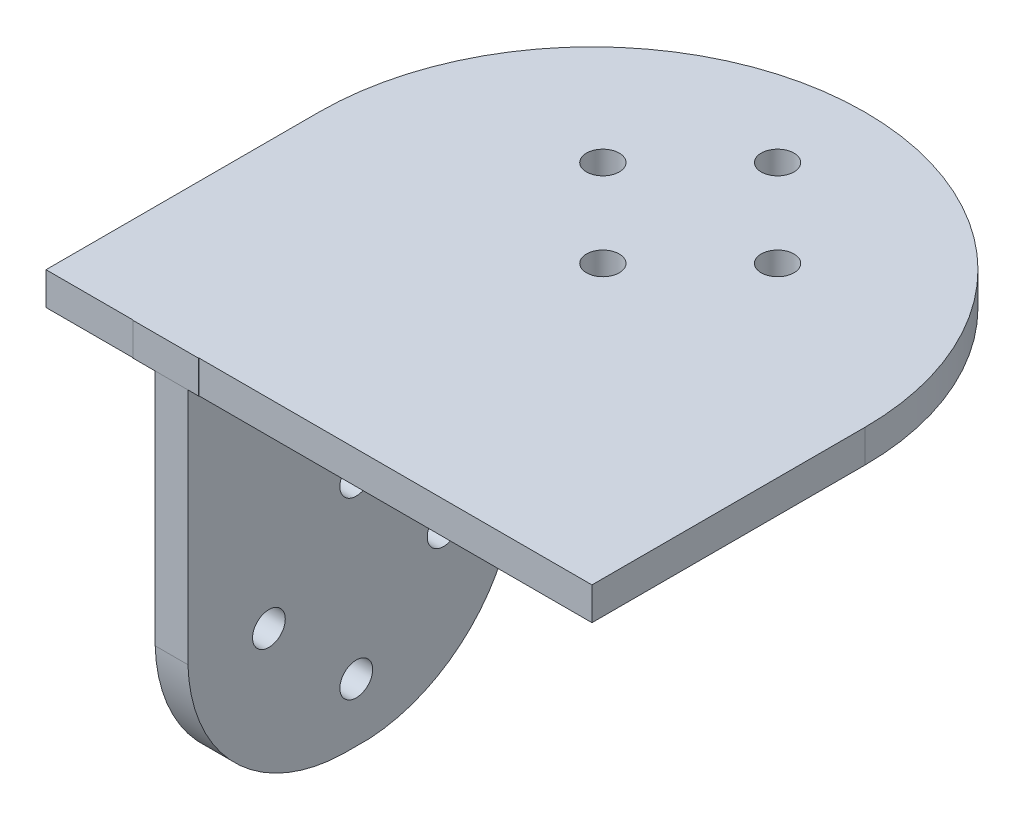
SolidWorks part; units mm, degrees
ref_plane "Plan de face" through (0, 0, 0) normal (0, 0, 1) x (1, 0, 0)
ref_plane "Plan de dessus" through (0, 0, 0) normal (0, 1, 0) x (1, 0, 0)
ref_plane "Plan de droite" through (0, 0, 0) normal (1, 0, 0) x (0, 0, -1)
sketch "Esquisse2" plane through (0, 0, 0) normal (0, 1, 0) x (1, 0, 0)
  line L0 (-25, 0) -> (25, 0) construction
  line L1 (-25, 0) -> (-25, -25)
  line L2 (25, 0) -> (25, -25)
  line L3 (25, -25) -> (-25, -25)
  arc A0 (25, 0) -> (-25, 0) centre (0, 0) ccw
  dimension "D1" = 50
  dimension "D2" = 25
  dimension "D3" = 25
extrude "Boss.-Extru.1" add sketch "Esquisse2" along normal blind 3
sketch "Esquisse4" plane through (0, 0, 0) normal (0, -1, 0) x (1, 0, 0)
  line L0 (-25, 25) -> (-15, 25) construction
  line L1 (-25, 25) -> (25, 25) construction
  line L2 (-15, 25) -> (-11, 25)
  line L7 (-15, 25) -> (-15, 0)
  line L8 (-15, 0) -> (-11, 0)
  line L9 (-11, 0) -> (-11, 25)
  dimension "D1" = 10
  dimension "D2" = 4
extrude "Enlèv. mat.-Extru.1" cut sketch "Esquisse4" against normal blind 3
sketch "Esquisse5" plane through (0, 0, 0) normal (0, -1, 0) x (1, 0, 0)
  line L0 (0, -25) -> (0, -23) construction
  line L1 (0, -23) -> (0, -20) construction
  line L2 (0, -20) -> (0, 2) construction
  line L3 (0, 2) -> (0, 5) construction
  line L4 (0, -9) -> (-30.2244, -9) construction
  line L5 (-30.2244, -9) -> (30.2203, -9) construction
  line L6 (30.2203, -9) -> (0, -9) construction
  line L7 (0, -9) -> (-12.5953, -21.5953) construction
  line L8 (0, -9) -> (12.5953, -21.5953) construction
  line L9 (0, -9) -> (-6.5, -9)
  line L10 (0, -9) -> (6.5, -9)
  line L11 (0, -9) -> (0, -2.5)
  line L12 (0, -9) -> (0, -15.5)
  line L13 (6.5, -9) -> (8, -9)
  line L14 (0, -15.5) -> (0, -17)
  line L15 (-6.5, -9) -> (-8, -9)
  line L16 (0, -2.5) -> (0, -1)
  arc A0 (-25, 0) -> (25, 0) centre (0, 0) ccw construction
  circle A5 centre (8, -9) radius 1.5
  circle A6 centre (-8, -9) radius 1.5
  circle A7 centre (0, -17) radius 1.5
  circle A8 centre (0, -1) radius 1.5
  dimension "D1" = 2
  dimension "D2" = 3
  dimension "D3" = 22
  dimension "D4" = 3
  dimension "D5" = 6.5
  dimension "D6" = 6.5
  dimension "D7" = 6.5
  dimension "D8" = 6.5
extrude "Enlèv. mat.-Extru.2" cut sketch "Esquisse5" against normal blind 3
sketch "Esquisse9" plane through (-15, 0, 0) normal (1, 0, 0) x (0, 0, -1)
  line L0 (-25, 3) -> (-25, 0)
  line L1 (-25, 3) -> (0.089, 3)
  line L2 (-25, 0) -> (0.089, 0)
  line L3 (0.089, 3) -> (0.089, 0)
extrude "Boss.-Extru.5" add sketch "Esquisse9" along normal blind 6
sketch "Esquisse10" plane through (0, 0, 0) normal (0, -1, 0) x (1, 0, 0)
  line L0 (-25, 25) -> (-15, 25)
  line L1 (-25, 25) -> (25, 25) construction
  line L2 (-15, 25) -> (-15, -5)
  line L3 (-15, -5) -> (-12, -5)
  line L4 (-12, -5) -> (-12, 25)
  line L5 (-12, 25) -> (-15, 25)
  line M2 (25, 25) -> (-25, 25)
extrude "Boss.-Extru.6" add sketch "Esquisse10" along normal blind 36 contours L3 L4 L2 M2
sketch "Esquisse12" plane through (-12, 0, 0) normal (1, 0, 0) x (0, 0, 1)
  line L0 (-5, 36) -> (-5, 0) construction
  line L1 (-5, 36) -> (25, 36) construction
  line L2 (25, 36) -> (25, 0) construction
  line L3 (-5, 22.6624) -> (-5, 36)
  line L4 (-5, 36) -> (25, 36)
  line L5 (25, 36) -> (25, 21.8312)
  arc A0 (-5, 22.6624) -> (10, 36) centre (9.1688, 21.8312) cw
  circle A5 centre (17.5856, 22.6624) radius 1.5
  circle A6 centre (1.5856, 22.6624) radius 1.5
  circle A7 centre (9.5856, 14.6624) radius 1.5
  circle A8 centre (9.5856, 30.6624) radius 1.5
  arc A9 (10, 36) -> (25, 21.8312) centre (10.4156, 21.4156) cw
  line M39 (25, 0) -> (25, 36)
  line M40 (25, 36) -> (-5, 36)
  line M41 (-5, 36) -> (-5, 0)
extrude "Enlèv. mat.-Extru.3" cut sketch "Esquisse12" against normal blind 36 contours A0 M41 M40 | A9 M40 M39 | A8 | A6 | A7 | A5
sketch "Esquisse6" plane through (-11, 0, 0) normal (-1, 0, 0) x (0, 0, 1)
  line L0 (25, 3) -> (25, -32)
  line L1 (25, 3) -> (0, 3) construction
  line L2 (0, 3) -> (25, 3) construction
  line L3 (25, 3) -> (25, -14.5) construction
  line L4 (25, 3) -> (12.5, 3) construction
  line L5 (12.5, 3) -> (12.5, -14.5) construction
  line L6 (12.5, -14.5) -> (25, -14.5) construction
  line L7 (25, -14.5) -> (0, -14.5) construction
  line L8 (0, -14.5) -> (0, 3)
  line L9 (0, 3) -> (25, 3)
  arc A0 (0, -14.5) -> (25, -14.5) centre (12.5, -14.5) ccw
  dimension "D1" = 35
  dimension "D2" = 25
  dimension "D3" = 17.5
sketch "Esquisse8" plane through (-11, 0, 0) normal (-1, 0, 0) x (0, 0, 1)
  line L0 (0, 0) -> (0, 3)
  line L1 (0, 0) -> (25.0333, 0)
  line L2 (0, 3) -> (25.0333, 3)
  line L3 (25.0333, 0) -> (25.0333, 3)
extrude "Boss.-Extru.4" add sketch "Esquisse8" along normal blind 6
